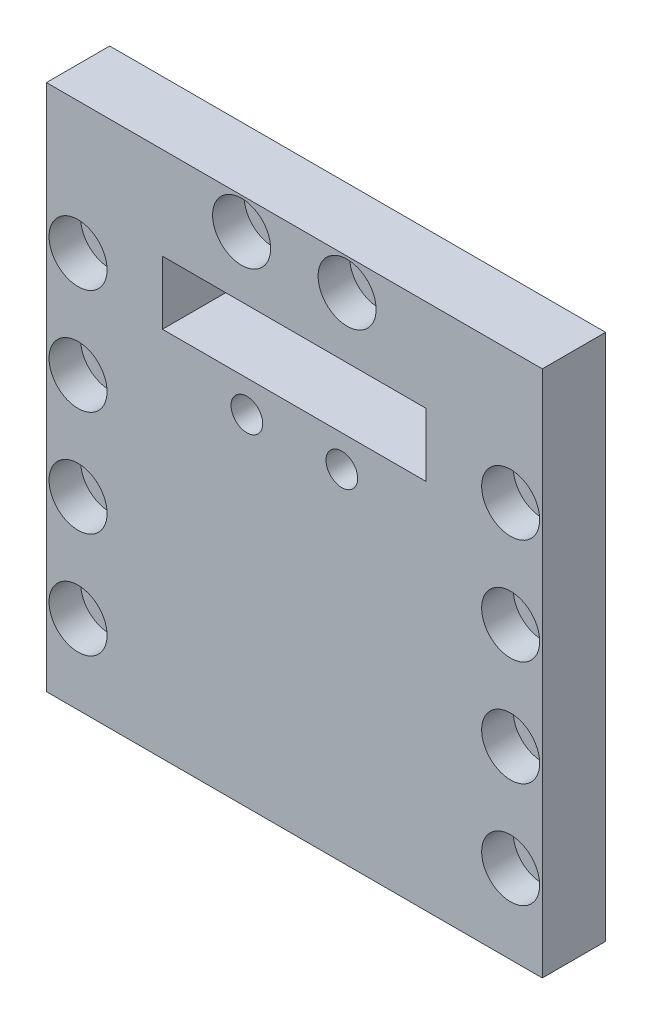
SolidWorks part; units mm, degrees
ref_plane "前视基准面" through (0, 0, 0) normal (0, 0, 1) x (1, 0, 0)
ref_plane "上视基准面" through (0, 0, 0) normal (0, 1, 0) x (1, 0, 0)
ref_plane "右视基准面" through (0, 0, 0) normal (1, 0, 0) x (0, 0, -1)
sketch "草图1" plane through (0, 0, 0) normal (0, 0, 1) x (1, 0, 0)
  line L0 (0, 0) -> (0, 27.0519) construction
  line L1 (-47, -50) -> (47, -50)
  line L2 (-47, -50) -> (-47, 50)
  line L3 (-47, 50) -> (47, 50)
  line L4 (47, -50) -> (47, 50)
  line L5 (-47, -50) -> (47, 50) construction
  line L6 (-47, 50) -> (47, -50) construction
  line L7 (-41, -35) -> (-41, -15) construction
  line L9 (-25, 32.5) -> (25, 32.5)
  line L10 (-25, 32.5) -> (-25, 20.5)
  line L11 (-25, 20.5) -> (25, 20.5)
  line L12 (25, 32.5) -> (25, 20.5)
  line L13 (-25, 32.5) -> (25, 20.5) construction
  line L14 (-25, 20.5) -> (25, 32.5) construction
  circle A0 centre (10, 44) radius 3
  circle A1 centre (-10, 44) radius 3
  circle A2 centre (-41, -35) radius 3
  circle A3 centre (-41, -15) radius 3
  circle A4 centre (-41, 5) radius 3
  circle A5 centre (-41, 25) radius 3
  circle A6 centre (41, -35) radius 3
  circle A7 centre (41, -15) radius 3
  circle A8 centre (41, 5) radius 3
  circle A9 centre (41, 25) radius 3
  circle A10 centre (-9, 14.5) radius 3
  circle A11 centre (9, 14.5) radius 3
  point P0 (0, 0)
  point P30 (0, 26.5)
  dimension "D3" = 6
  dimension "D5" = 6
  dimension "D6" = 6
  dimension "D9" = 6
  dimension "D17" = 6
  dimension "D18" = 6
  dimension "D20" = 6
  dimension "D1" = 100
  dimension "D2" = 94
  dimension "D4" = 6
  dimension "D7" = 37
  dimension "D8" = 37
  dimension "D10" = 6
  dimension "D11" = 15
  dimension "D13" = 20
  dimension "D14" = 12
  dimension "D15" = 50
  dimension "D16" = 23.5
  dimension "D19" = 6
  dimension "D21" = 9
  dimension "D22" = 9
  dimension "D12" = 4
extrude "凸台-拉伸1" add sketch "草图1" along normal blind 12
sketch "草图2" plane through (0, 0, 12) normal (0, 0, 1) x (1, 0, 0)
  line L0 (0, 0) -> (0, -36.8708) construction
  circle A2 centre (-10, 44) radius 5.5
  circle A3 centre (-10, 44) radius 5.5
  circle A5 centre (-41, 25) radius 5.5
  circle A6 centre (-41, 25) radius 5.5
  circle A8 centre (-41, 5) radius 5.5
  circle A9 centre (-41, 5) radius 5.5
  circle A11 centre (-41, -15) radius 5.5
  circle A12 centre (-41, -15) radius 5.5
  circle A13 centre (41, -35) radius 5.5
  circle A14 centre (-41, -35) radius 5.5
  circle A15 centre (-41, -35) radius 5.5
  circle A16 centre (41, -15) radius 5.5
  circle A17 centre (41, 5) radius 5.5
  circle A18 centre (41, 25) radius 5.5
  circle A19 centre (10, 44) radius 5.5
  dimension "D1" = 2.5
  dimension "D2" = 2.5
  dimension "D3" = 2.5
  dimension "D4" = 2.5
  dimension "D5" = 2.5
extrude "切除-拉伸1" cut sketch "草图2" against normal blind 6
sketch "草图3" plane through (0, -50, 0) normal (0, -1, 0) x (1, 0, 0)
  line L0 (0, 0) -> (0, 12) construction
  line L1 (-47, 0) -> (47, 0) construction
  line L2 (-47, 12) -> (47, 12) construction
  line L3 (-47, 12) -> (-47, 0) construction
  circle A0 centre (-33, 6) radius 3
  circle A1 centre (-8, 6) radius 3
  circle A2 centre (33, 6) radius 3
  circle A3 centre (8, 6) radius 3
  dimension "D1" = 6
  dimension "D2" = 6
  dimension "D3" = 25
  dimension "D4" = 14
extrude "切除-拉伸2" cut sketch "草图3" against normal blind 10
